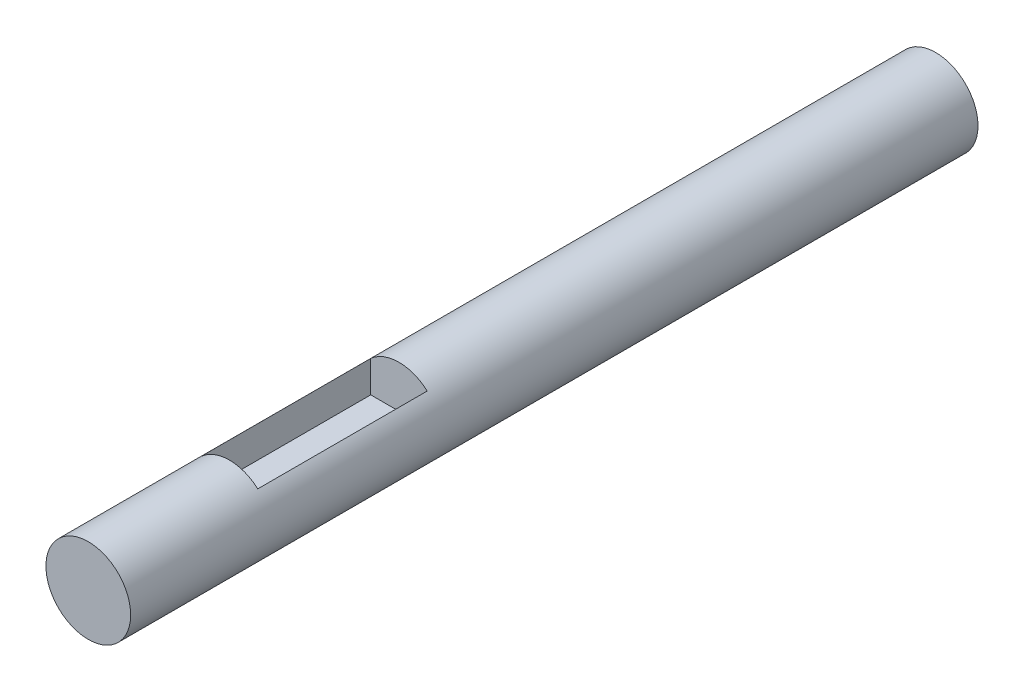
SolidWorks part; units mm, degrees
material "Alloy Steel"
ref_plane "Front Plane" through (0, 0, 0) normal (0, 0, 1) x (1, 0, 0)
ref_plane "Top Plane" through (0, 0, 0) normal (0, 1, 0) x (1, 0, 0)
ref_plane "Right Plane" through (0, 0, 0) normal (1, 0, 0) x (0, 0, -1)
sketch "Sketch1" plane through (0, 0, 0) normal (0, 0, 1) x (1, 0, 0)
  circle A0 centre (0, 0) radius 3
  dimension "D1" = 6
extrude "Boss-Extrude1" add sketch "Sketch1" along normal blind 60
ref_plane "Plane1" through (0, 3, 0) normal (0, 1, 0) x (1, 0, 0)
sketch "Sketch2" plane through (0, 3, 0) normal (0, 1, 0) x (1, 0, 0)
  line L0 (0, -60) -> (0, 0) construction
  line L1 (-3, -60) -> (3, -60) construction
  line L3 (-2, -50) -> (2, -50)
  line L4 (-2, -50) -> (-2, -38)
  line L5 (-2, -38) -> (2, -38)
  line L6 (2, -50) -> (2, -38)
  line L7 (-2, -50) -> (2, -38) construction
  line L8 (-2, -38) -> (2, -50) construction
  point P5 (0, -44)
  dimension "D1" = 12
  dimension "D2" = 4
  dimension "D3" = 16
extrude "Cut-Extrude1" cut sketch "Sketch2" against normal blind 3
equation "\"shaft-diameter\" =20mm"
equation "\"key-length\"=12mm"
equation "\"key-width\"=4mm"
equation "\"flippershaft-wormgear-diameter\" = 35mm"
equation "\"shaft-ring-groove-depth\"=0.5mm"
equation "\"shaft-ring-groove-width\" = 1.3mm"
equation "\"D1@Sketch2\"=\"key-length\""
equation "\"D2@Sketch2\"=\"key-width\""
